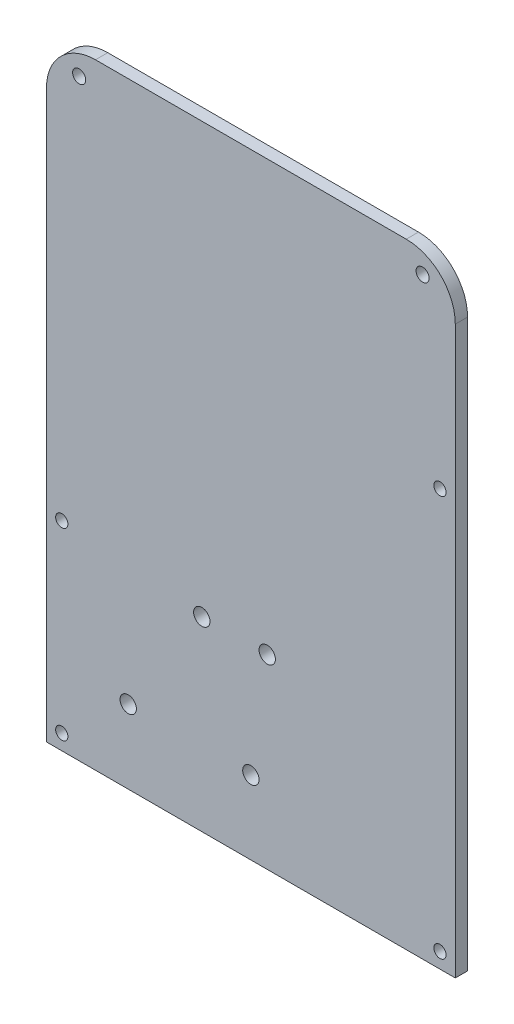
SolidWorks part; units mm, degrees
material "Polylactide (PLA)"
ref_plane "Front Plane" through (0, 0, 0) normal (0, 0, 1) x (1, 0, 0)
ref_plane "Top Plane" through (0, 0, 0) normal (0, 1, 0) x (1, 0, 0)
ref_plane "Right Plane" through (0, 0, 0) normal (1, 0, 0) x (0, 0, -1)
sketch "Sketch1" plane through (0, 0, 0) normal (0, 0, 1) x (1, 0, 0)
  line L1 (-160.5348, -113.268) -> (-60.5348, -113.268)
  line L2 (-160.5348, -113.268) -> (-160.5348, 37.232)
  line L3 (-160.5348, 37.232) -> (-60.5348, 37.232)
  line L4 (-60.5348, -113.268) -> (-60.5348, 37.232)
extrude "Boss-Extrude1" add sketch "Sketch1" along normal blind 3
sketch "Sketch2" plane through (0, 0, 3) normal (0, 0, 1) x (1, 0, 0)
  line L1 (-160.5348, 37.232) -> (-160.5348, -113.268) construction
  line L2 (-60.5348, -113.268) -> (-60.5348, 37.232) construction
  line L3 (-160.5348, -113.268) -> (-60.5348, -113.268) construction
  circle A2 centre (-156.7848, -109.518) radius 1.5
  circle A3 centre (-64.2848, -109.518) radius 1.5
  circle A4 centre (-64.2848, -11.518) radius 1.5
  circle A5 centre (-156.7848, -64.518) radius 1.5
  dimension "D5" = 3.75
  dimension "D10" = 45
  dimension "D6" = 3.75
  dimension "D7" = 3.75
  dimension "D8" = 3.75
extrude "Cut-Extrude1" cut sketch "Sketch2" against normal blind 3
sketch "Sketch3" plane through (0, 0, 3) normal (0, 0, 1) x (1, 0, 0)
  line L0 (-160.5348, -113.268) -> (-60.5348, -113.268) construction
  line L1 (-160.5348, 37.232) -> (-160.5348, -113.268) construction
  circle A0 centre (-140.5348, -95.268) radius 2
  circle A1 centre (-110.5348, -95.268) radius 2
  circle A2 centre (-106.5348, -67.768) radius 2
  circle A3 centre (-122.5348, -67.768) radius 2
  dimension "D1" = 18
  dimension "D3" = 30
  dimension "D5" = 27.5
  dimension "D7" = 16
  dimension "D2" = 20
  dimension "D4" = 18
  dimension "D6" = 4
extrude "Cut-Extrude2" cut sketch "Sketch3" against normal blind 3
fillet "Fillet1" radius 12 2 edges at (-160.5348, 37.232, 1.5) (-60.5348, 37.232, 1.5)
sketch "Sketch4" plane through (0, 0, 3) normal (0, 0, 1) x (1, 0, 0)
  line L0 (-72.5348, 37.232) -> (-148.5348, 37.232) construction
  line L1 (-60.5348, -113.268) -> (-60.5348, 25.232) construction
  circle A0 centre (-152.5348, 31.732) radius 1.6
  circle A1 centre (-68.5348, 31.732) radius 1.6
  dimension "D1" = 5.5
  dimension "D2" = 8
  dimension "D3" = 5.5
  dimension "D4" = 8
extrude "Cut-Extrude3" cut sketch "Sketch4" against normal blind 10
